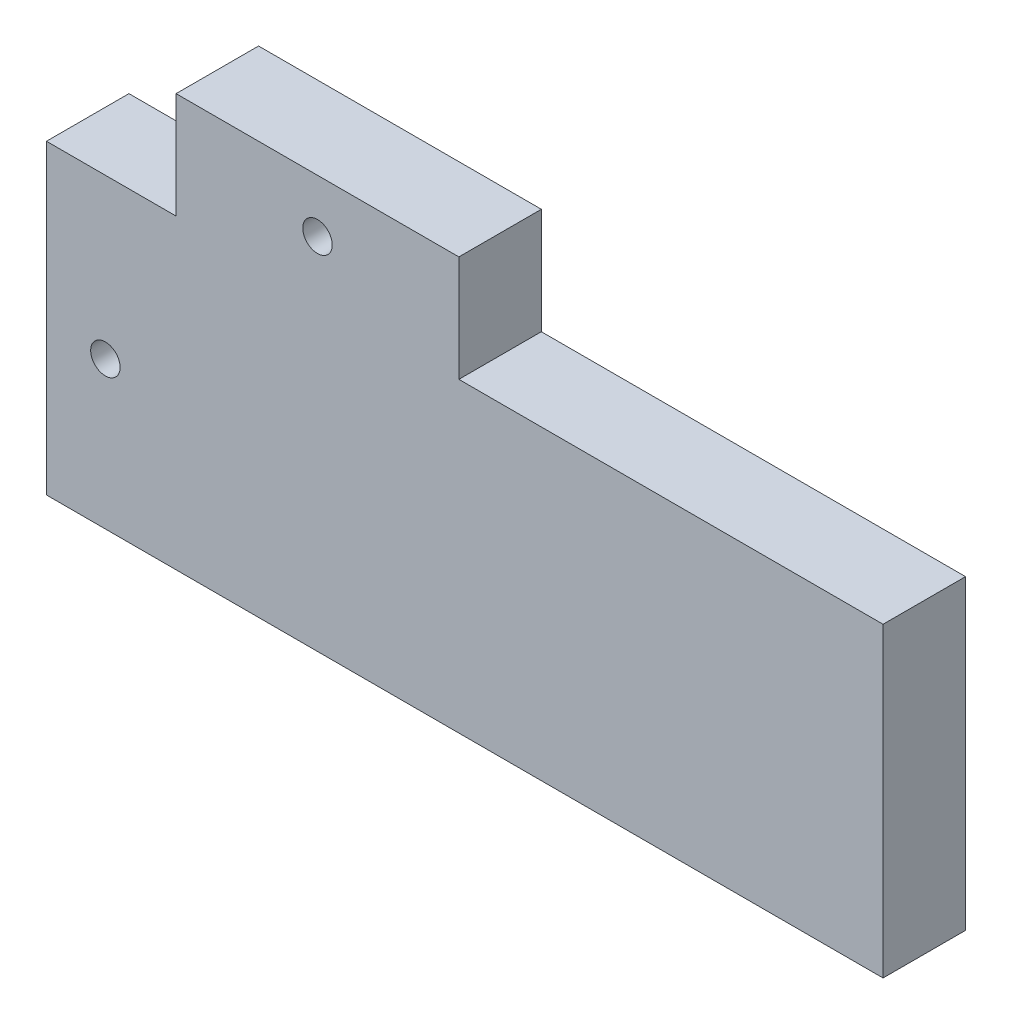
SolidWorks part; units mm, degrees
ref_plane "Front" through (0, 0, 0) normal (0, 0, 1) x (1, 0, 0)
ref_plane "Top" through (0, 0, 0) normal (0, 1, 0) x (1, 0, 0)
ref_plane "Right" through (0, 0, 0) normal (1, 0, 0) x (0, 0, -1)
sketch "Sketch1" plane through (0, 0, 0) normal (0, 0, 1) x (1, 0, 0)
  line L9 (-28, -13) -> (28, -13)
  line L10 (-28, -13) -> (-28, 13)
  line L11 (-28, 13) -> (28, 13)
  line L12 (28, -13) -> (28, 13)
  line L13 (-28, -13) -> (28, 13) construction
  line L14 (-28, 13) -> (28, -13) construction
  line L15 (-17, 13) -> (7, 13)
  line L16 (-17, 13) -> (-17, 22)
  line L17 (-17, 22) -> (7, 22)
  line L18 (7, 13) -> (7, 22)
  point P0 (0, 0)
  dimension "D1" = 56
  dimension "D2" = 26
  dimension "D3" = 9
  dimension "D4" = 24
  dimension "D5" = 11
extrude "Boss-Extrude1" add sketch "Sketch1" along normal blind 7 contours L9 L12 L11 L10 | L11 L18 L17 L16
sketch "Sketch2" plane through (0, 0, 7) normal (0, 0, 1) x (1, 0, 0)
  line L0 (7, 13) -> (7, 22) construction
  line L1 (-17, 22) -> (7, 22) construction
  circle A0 centre (-5, 17.5) radius 1.25
  circle A1 centre (-23, -0.5) radius 1.25
  dimension "D3" = 2.5
  dimension "D1" = 12
  dimension "D2" = 4.5
  dimension "D4" = 18
  dimension "D5" = 18
extrude "Cut-Extrude1" cut sketch "Sketch2" against normal blind 7
sketch "Sketch3" plane through (0, 0, 0) normal (0, 0, -1) x (-1, 0, 0)
  circle A0 centre (-5.25, 7.25) radius 2.65
  circle A1 centre (-19.25, 7.25) radius 2.65
  circle A2 centre (5, 17.5) radius 1.25 construction
  point P6 (0, 0)
  dimension "D3" = 5.3
  dimension "D1" = 10.25
  dimension "D2" = 10.25
  dimension "D4" = 14
extrude "Cut-Extrude2" cut sketch "Sketch3" against normal blind 4.6
sketch "Sketch4" plane through (28, 0, 0) normal (1, 0, 0) x (0, 0, -1)
  line L1 (-7, 13) -> (0, 13)
  line L2 (-7, 13) -> (-7, -13)
  line L3 (-7, -13) -> (0, -13)
  line L4 (0, 13) -> (0, -13)
extrude "Boss-Extrude2" add sketch "Sketch4" along normal blind 15
